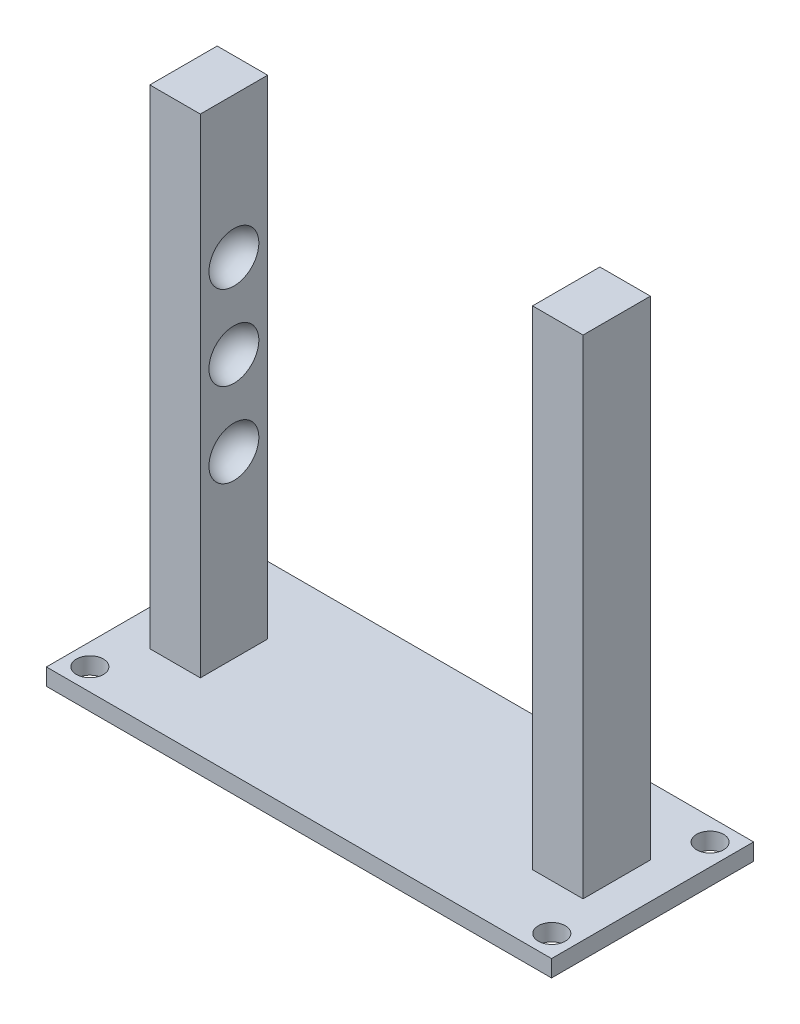
SolidWorks part; units mm, degrees
ref_plane "前视基准面" through (0, 0, 0) normal (0, 0, 1) x (1, 0, 0)
ref_plane "上视基准面" through (0, 0, 0) normal (0, 1, 0) x (1, 0, 0)
ref_plane "右视基准面" through (0, 0, 0) normal (1, 0, 0) x (0, 0, -1)
other "Configuration Table"
sketch "草图2" plane through (0, 0, 0) normal (0, 1, 0) x (1, 0, 0)
  line L1 (-115.4764, 40.5388) -> (34.5236, 40.5388)
  line L2 (-115.4764, 40.5388) -> (-115.4764, -19.4612)
  line L3 (-115.4764, -19.4612) -> (34.5236, -19.4612)
  line L4 (34.5236, 40.5388) -> (34.5236, -19.4612)
  dimension "D1" = 60
  dimension "D2" = 150
extrude "凸台-拉伸1" add sketch "草图2" along normal blind 5
sketch "草图3" plane through (0, 0, 0) normal (0, 1, 0) x (1, 0, 0)
  line L1 (-104.8025, 20.5724) -> (-89.8025, 20.5724)
  line L2 (-104.8025, 20.5724) -> (-104.8025, 0.5724)
  line L3 (-104.8025, 0.5724) -> (-89.8025, 0.5724)
  line L4 (-89.8025, 20.5724) -> (-89.8025, 0.5724)
  dimension "D3" = 15
  dimension "D4" = 20
extrude "凸台-拉伸2" add sketch "草图3" along normal blind 150
sketch "草图17" plane through (0, 5, 0) normal (0, 1, 0) x (1, 0, 0)
  line L0 (-40.4764, 40.5388) -> (-40.4764, -19.4612) construction
  line L1 (34.5236, 40.5388) -> (-115.4764, 40.5388) construction
  line L2 (-115.4764, -19.4612) -> (34.5236, -19.4612) construction
ref_plane "基准面1" through (-40.4764, 0, 0) normal (1, 0, 0) x (0, 0, -1)
sketch "草图18" plane through (0, 5, 0) normal (0, 1, 0) x (1, 0, 0)
  line L0 (-115.4764, 10.5388) -> (34.5236, 10.5388) construction
  line L1 (-115.4764, 40.5388) -> (-115.4764, -19.4612) construction
  line L2 (34.5236, -19.4612) -> (34.5236, 40.5388) construction
ref_plane "基准面2" through (0, 0, -10.5388) normal (0, 0, 1) x (1, 0, 0)
sketch "草图19" plane through (0, 0, -10.5388) normal (0, 0, 1) x (1, 0, 0)
  line L0 (-89.8025, 90.5762) -> (-89.8025, 75.7718)
  line L1 (-89.8025, 150) -> (-89.8025, 5) construction
  arc A0 (-89.8025, 90.5762) -> (-89.8025, 75.7718) centre (-89.8025, 83.174) ccw
  dimension "D1" = 0
revolve "切除-旋转29" cut sketch "草图19" angle 360 about L0
pattern_linear "阵列(线性)1" count 2 spacing 25 along (0, 1, 0) count 2 spacing 25 along (0, -1, 0) of "切除-旋转29"
sketch "草图22" plane through (0, 0, 0) normal (0, 1, 0) x (1, 0, 0)
  line L0 (34.5236, 40.5388) -> (-115.4764, 40.5388) construction
  circle A0 centre (-109.0629, 34.0388) radius 4
  point P2 (0, 0)
  point P3 (0, 0)
  point P4 (-108.1869, 32.7878)
  point P5 (-109.0629, 34.0141)
  dimension "D1" = 8
  dimension "D2" = 6.5
extrude "切除-拉伸3" cut sketch "草图22" along normal blind 5
mirror "镜向18" about plane through (0, 0, -10.5388) normal (0, 0, 1) of "切除-拉伸3"
mirror "镜向19" about plane through (-40.4764, 0, 0) normal (1, 0, 0) of "镜向18", "切除-拉伸3"
mirror "镜向20" about plane through (-40.4764, 0, 0) normal (1, 0, 0) of "凸台-拉伸2"
mirror "镜向21" about plane through (-40.4764, 0, 0) normal (1, 0, 0) of "切除-旋转29"
mirror "镜向22" about plane through (-40.4764, 0, 0) normal (1, 0, 0) of "阵列(线性)1"
